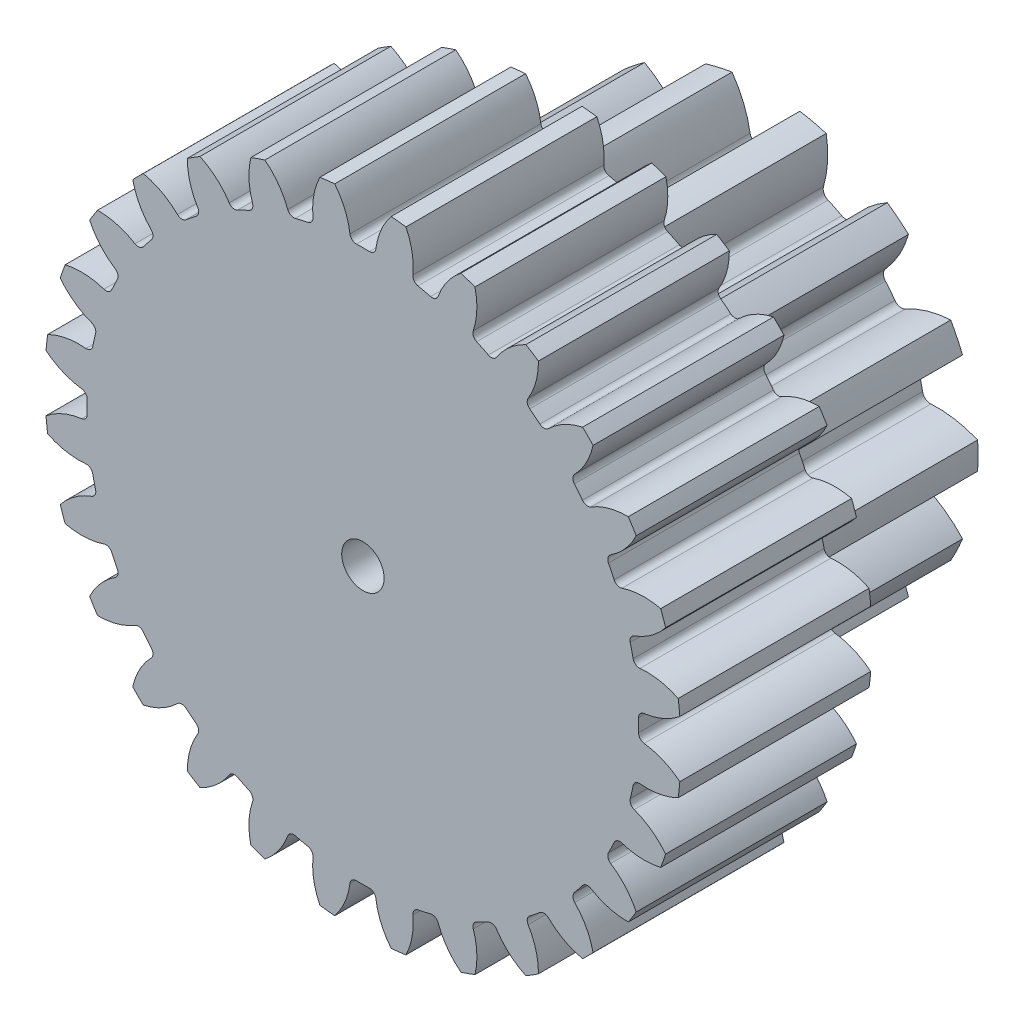
SolidWorks part; units mm, degrees
ref_plane "Front" through (0, 0, 0) normal (0, 0, 1) x (1, 0, 0)
ref_plane "Top" through (0, 0, 0) normal (0, 1, 0) x (1, 0, 0)
ref_plane "Right" through (0, 0, 0) normal (1, 0, 0) x (0, 0, -1)
sketch "Sketch1" plane through (0, 0, 0) normal (0, 0, 1) x (1, 0, 0)
  circle A0 centre (0, 0) radius 7.5
  circle A1 centre (0, 0) radius 10
  circle A2 centre (0, 0) radius 8.75
  dimension "D1" = 20
  dimension "D2" = 15
  dimension "D3" = 17.5
extrude "Boss-Extrude1" add sketch "Sketch1" along normal mid plane 10 contours A1
sketch "Sketch3" plane through (0, 0, 0) normal (0, 0, 1) x (1, 0, 0)
  line L0 (0, 0) -> (0, 10) construction
  line L1 (-0.9797, 8.695) -> (0.9797, 8.695) construction
  line L2 (-1.7667, 10.8572) -> (0, 6.0033) construction
  line L3 (0, 0) -> (2.2252, 9.7493) construction
  line L4 (0.9797, 8.695) -> (2.8899, 8.259) construction
  line L5 (0, 0) -> (-0.7032, 7.467) construction
  circle A0 centre (0, 0) radius 10 construction
  arc A1 (-2.385, 10.7383) -> (-0.7032, 7.467) centre (-5.6278, 7.0032) cw
  arc A2 (2.385, 10.7383) -> (0.7032, 7.467) centre (5.6278, 7.0032) ccw
  arc A3 (0.7032, 7.467) -> (-0.7032, 7.467) centre (0, 0) ccw
  circle A4 centre (0, 0) radius 7.5 construction
  circle A6 centre (0, 0) radius 8.75 construction
  circle A7 centre (0, 0) radius 11
  arc A8 (2.385, 10.7383) -> (-2.385, 10.7383) centre (0, 0) ccw
  circle A9 centre (0, 0) radius 10 construction
  dimension "D3" = 12.857
  dimension "D2" = 20
  dimension "D1" = 1
extrude "Cut-Extrude1" cut sketch "Sketch3" against normal through all both and the other way through all
fillet "Fillet2" radius 0.375 2 edges at (0.7032, 7.467, 0) (-0.7032, 7.467, 0)
pattern_circular "CirPattern1" count 14 over 360 about axis through (0, 0, 0) along (0, 0, 1) of "Cut-Extrude1", "Fillet2"
sketch "Sketch4" plane through (0, 0, 5) normal (0, 0, 1) x (1, 0, 0)
  circle A0 centre (0, 0) radius 14
  circle A1 centre (0, 0) radius 15
  circle A2 centre (0, 0) radius 13
  dimension "D1" = 28
  dimension "D2" = 30
  dimension "D3" = 26
extrude "Boss-Extrude2" add sketch "Sketch4" along normal blind 9 separate body
sketch "Sketch5" plane through (0, 0, 14) normal (0, 0, 1) x (1, 0, 0)
  line L0 (0, 0) -> (0, 15) construction
  line L1 (-0.785, 13.978) -> (0.785, 13.978) construction
  line L2 (-0.587, 12.9867) -> (0, 0) construction
  line L3 (-1.4955, 15.93) -> (0, 11.8212) construction
  line L4 (0, 0) -> (1.6795, 14.9057) construction
  line L5 (0.785, 13.978) -> (2.3451, 13.8022) construction
  circle A0 centre (0, 0) radius 15 construction
  arc A1 (-2.4172, 15.8164) -> (-0.587, 12.9867) centre (-3.9226, 12.836) cw
  arc A2 (2.4172, 15.8164) -> (0.587, 12.9867) centre (3.9226, 12.836) ccw
  circle A3 centre (0, 0) radius 13 construction
  arc A4 (0.587, 12.9867) -> (-0.587, 12.9867) centre (0, 0) ccw
  circle A6 centre (0, 0) radius 14 construction
  circle A7 centre (0, 0) radius 16
  arc A8 (2.4172, 15.8164) -> (-2.4172, 15.8164) centre (0, 0) ccw
  circle A9 centre (0, 0) radius 15 construction
  dimension "D2" = 20
  dimension "D1" = 1
  dimension "D3" = 6.429
extrude "Cut-Extrude2" cut sketch "Sketch5" against normal up to surface (9 mm away) up to face at (15, 0, 5)
fillet "Fillet3" radius 0.3 2 edges at (0.587, 12.9867, 9.5) (-0.587, 12.9867, 9.5)
pattern_circular "CirPattern2" count 28 over 360 about axis through (0, 0, 0) along (0, 0, 1) of "Cut-Extrude2", "Fillet3"
sketch "Sketch6" plane through (0, 0, 14) normal (0, 0, 1) x (1, 0, 0)
  circle A0 centre (0, 0) radius 1
  dimension "D1" = 2
extrude "Cut-Extrude3" cut sketch "Sketch6" against normal through all
equation "\"bot_n\"= 14'bottom number of teeth"
equation "\"bot_m\"= \"bot_od\" / ( \"bot_n\" + 2 )'bottom module"
equation "\"bot_p\"= \"bot_m\" * pi'bottom pitch"
equation "\"bot_d\"= \"bot_m\" * \"bot_n\"'bottom primitive diameter"
equation "\"bot_da\"= \"bot_d\" + 2 * \"bot_m\"'bottom head diamater"
equation "\"bot_df\"= \"bot_d\" - 2 * \"bot_m\"'bottom foot diameter"
equation "\"bot_od\"= 20'bottom outer diameter"
equation "\"D1@Sketch1\"=\"bot_od\""
equation "\"D2@Sketch1\"=\"bot_df\""
equation "\"D3@Sketch1\"=\"bot_d\""
equation "\"D3@Sketch3\"= 180 / \"bot_n\""
equation "\"D1@Fillet2\"=.3*\"bot_m\""
equation "\"top_n\" = 28'top number of teeth"
equation "\"top_od\" = 30'top outer diameter"
equation "\"top_m\"= \"top_od\" / ( \"top_n\" + 2 )'top module"
equation "\"top_p\"= \"top_m\" * pi'top pitch"
equation "\"top_d\"= \"top_m\" * \"top_n\"'top primitive diameter"
equation "\"top_da\"= \"top_d\" + 2 * \"top_m\"'top head diameter"
equation "\"top_df\"= \"top_d\" - 2 * \"top_m\"'top foot diamter"
equation "\"D1@CirPattern1\"= \"bot_n\""
equation "\"D1@Sketch4\"= \"top_m\" * \"top_n\""
equation "\"D2@Sketch4\"= (\"top_n\" + 2) * \"top_m\""
equation "\"D3@Sketch4\"=\"top_df\""
equation "\"D3@Sketch5\"= 180 / \"top_n\""
equation "\"D1@Fillet3\"=.3 * \"top_m\""
equation "\"D1@CirPattern2\"= \"top_n\""
